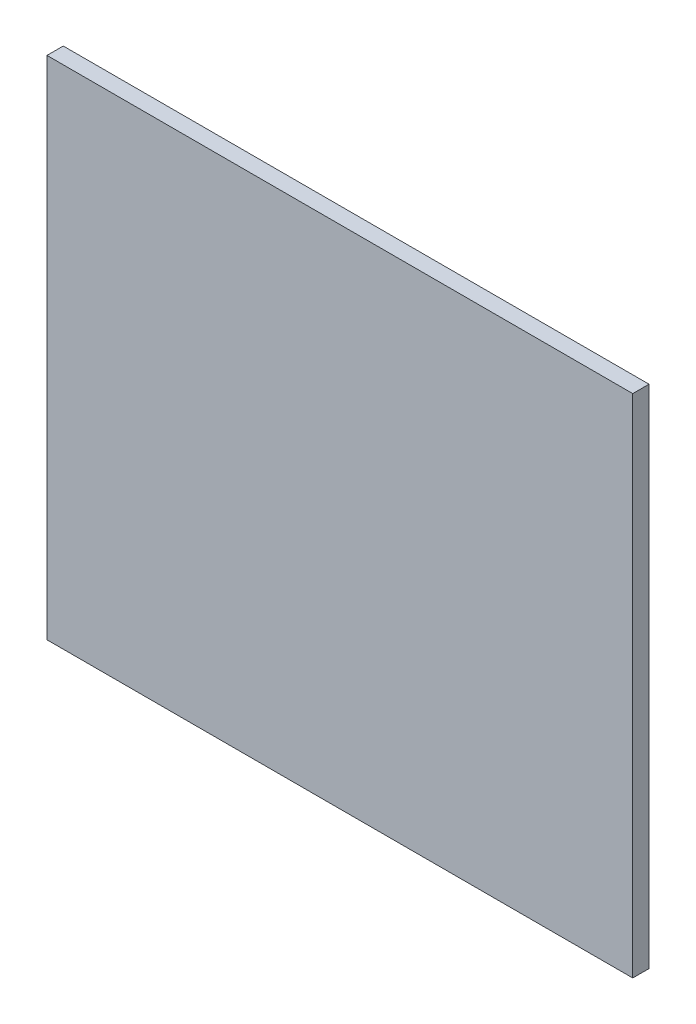
SolidWorks part; units mm, degrees
ref_plane "Спереди" through (0, 0, 0) normal (0, 0, 1) x (1, 0, 0)
ref_plane "Сверху" through (0, 0, 0) normal (0, 1, 0) x (1, 0, 0)
ref_plane "Справа" through (0, 0, 0) normal (1, 0, 0) x (0, 0, -1)
sketch "Эскиз1" plane through (0, 0, 0) normal (0, 0, 1) x (1, 0, 0)
  line L1 (0, 0) -> (71.9999, 0)
  line L2 (0, 0) -> (0, -62.2102)
  line L3 (0, -62.2102) -> (71.9999, -62.2102)
  line L4 (71.9999, 0) -> (71.9999, -62.2102)
extrude "Вытянуть1" add sketch "Эскиз1" along normal blind 2
